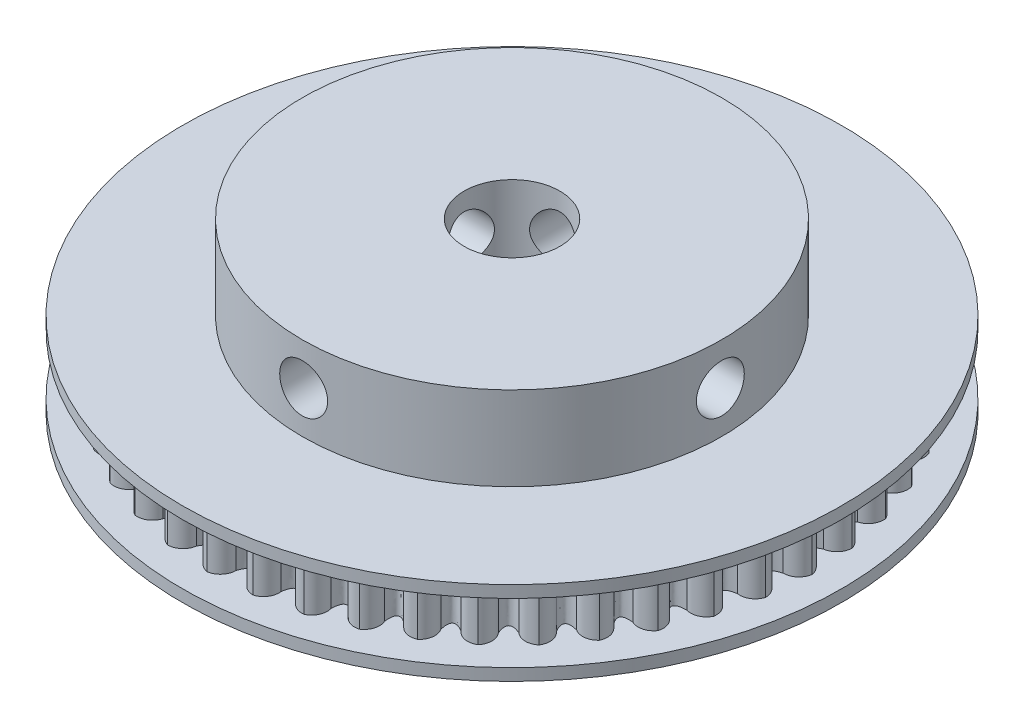
SolidWorks part; units mm, degrees
ref_plane "Front Plane" through (0, 0, 0) normal (0, 0, 1) x (1, 0, 0)
ref_plane "Top Plane" through (0, 0, 0) normal (0, 1, 0) x (1, 0, 0)
ref_plane "Right Plane" through (0, 0, 0) normal (1, 0, 0) x (0, 0, -1)
sketch "Sketch1" plane through (0, 0, 0) normal (0, 0, 1) x (1, 0, 0)
  line L0 (0, 0) -> (0, 9.8929) construction
  line L1 (5, 0) -> (25.25, 0)
  line L2 (25.25, 0) -> (25.25, 5)
  line L3 (25.25, 5) -> (5, 5)
  line L4 (5, 5) -> (5, 0)
  dimension "D1" = 5
  dimension "D2" = 5
  dimension "D3" = 20.25
revolve "Revolve1" add sketch "Sketch1" angle 360 about L0
sketch "Sketch2" plane through (0, 5, 0) normal (0, 1, 0) x (1, 0, 0)
  line L0 (0, 0) -> (0, 25.25) construction
  line L1 (0, 0) -> (4, 24.9312) construction
  line L2 (4, 24.9312) -> (0, 25.25) construction
  line L3 (2, 25.0906) -> (0, 0) construction
  line L4 (0, 25.25) -> (0, 27.3286)
  line L5 (0, 27.3286) -> (4.5433, 26.8333)
  line L6 (4.5433, 26.8333) -> (4, 24.9312)
  circle A0 centre (0, 0) radius 25.25 construction
  arc A1 (0, 25.25) -> (1.2998, 23.9283) centre (0, 23.95) cw
  arc A2 (4, 24.9312) -> (2.5072, 23.8321) centre (3.7941, 23.6476) ccw
  spline S0 degree 2 poles (1.2998, 23.9283) (1.7861, 22.4075) (2.5072, 23.8321) knots 0 0 0 1 1 1
  dimension "D2" = 1.3
  dimension "D3" = 2
  dimension "D1" = 4
extrude "Cut-Extrude2" cut sketch "Sketch2" against normal through all
pattern_circular "CirPattern1" count 44 over 360 about axis through (0, 0, 0) along (0, -1, 0) of "Cut-Extrude2"
sketch "Sketch3" plane through (0, 5, 0) normal (0, 1, 0) x (1, 0, 0)
  circle A0 centre (0, 0) radius 27.5
  dimension "D1" = 55
extrude "Boss-Extrude1" add sketch "Sketch3" along normal blind 1
sketch "Sketch4" plane through (0, 0, 0) normal (0, -1, 0) x (1, 0, 0)
  circle A0 centre (0, 0) radius 27.5
  dimension "D1" = 55
extrude "Boss-Extrude2" add sketch "Sketch4" along normal blind 1
sketch "Sketch5" plane through (0, 6, 0) normal (0, 1, 0) x (1, 0, 0)
  circle A0 centre (0, 0) radius 17.5
  dimension "D1" = 35
extrude "Boss-Extrude3" add sketch "Sketch5" along normal blind 7
sketch "Sketch6" plane through (0, 13, 0) normal (0, 1, 0) x (1, 0, 0)
  circle A0 centre (0, 0) radius 4
  dimension "D1" = 8
extrude "Cut-Extrude3" cut sketch "Sketch6" against normal through all
sketch "Sketch7" plane through (0, 0, 0) normal (1, 0, 0) x (0, 0, -1)
  line L0 (0, 13) -> (0, 6) construction
  line L1 (17.5, 13) -> (-17.5, 13) construction
  line L2 (27.5, 6) -> (-27.5, 6) construction
  circle A0 centre (0, 9.5) radius 2
  dimension "D1" = 4
extrude "Cut-Extrude4" cut sketch "Sketch7" against normal through all
pattern_circular "CirPattern2" count 4 over 360 about axis through (0, 13, 0) along (0, -1, 0) of "Cut-Extrude4"
